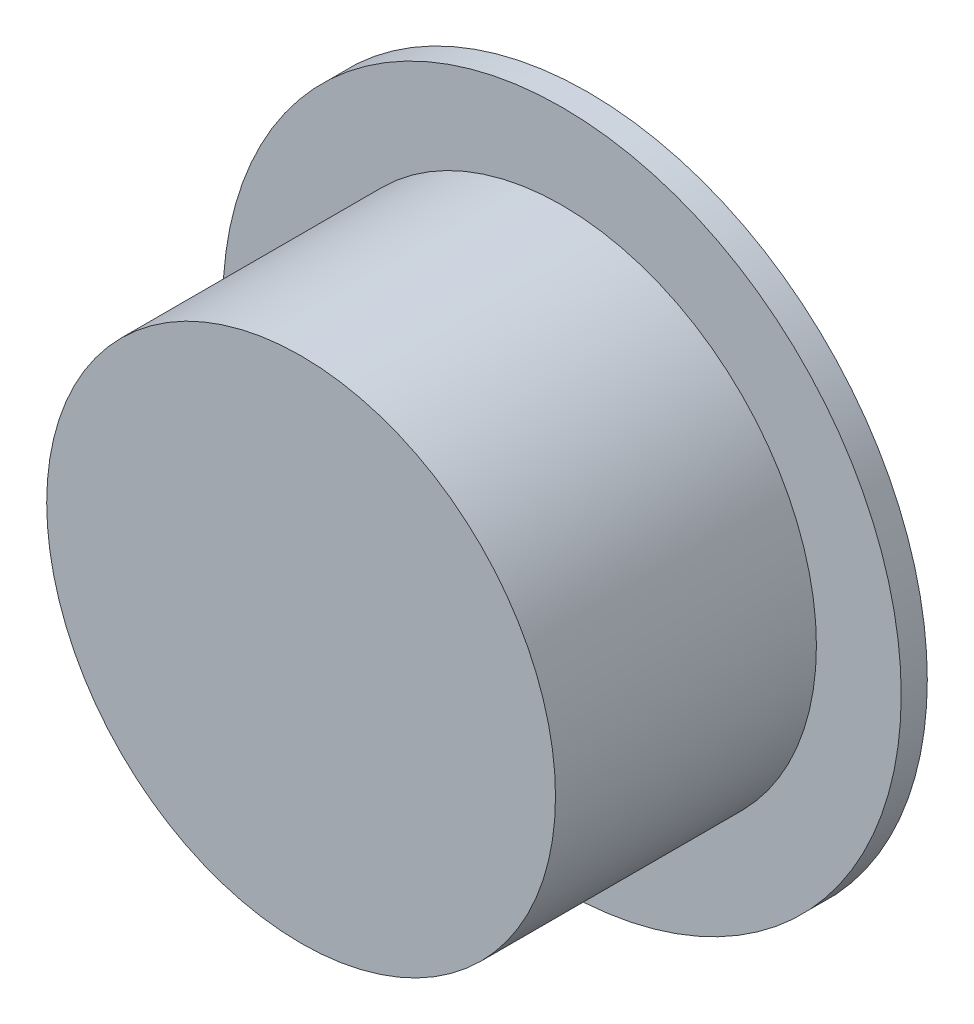
SolidWorks part; units mm, degrees
ref_plane "Front Plane" through (0, 0, 0) normal (0, 0, 1) x (1, 0, 0)
ref_plane "Top Plane" through (0, 0, 0) normal (0, 1, 0) x (1, 0, 0)
ref_plane "Right Plane" through (0, 0, 0) normal (1, 0, 0) x (0, 0, -1)
sketch "Sketch1" plane through (0, 0, 0) normal (0, 0, 1) x (1, 0, 0)
  circle A0 centre (0, 0) radius 4.875
  dimension "D1" = 9.75
extrude "Boss-Extrude1" add sketch "Sketch1" along normal blind 5
sketch "Sketch3" plane through (0, 0, 0) normal (0, 0, -1) x (-1, 0, 0)
  circle A0 centre (0, 0) radius 6.5
  dimension "D1" = 13
extrude "Boss-Extrude2" add sketch "Sketch3" along normal blind 0.5
sketch "Sketch5" plane through (0, 0, -0.5) normal (0, 0, -1) x (-1, 0, 0)
  circle A0 centre (0, 0) radius 1.75
  dimension "D1" = 3.5
extrude "Cut-Extrude1" cut sketch "Sketch5" against normal blind 0.75
